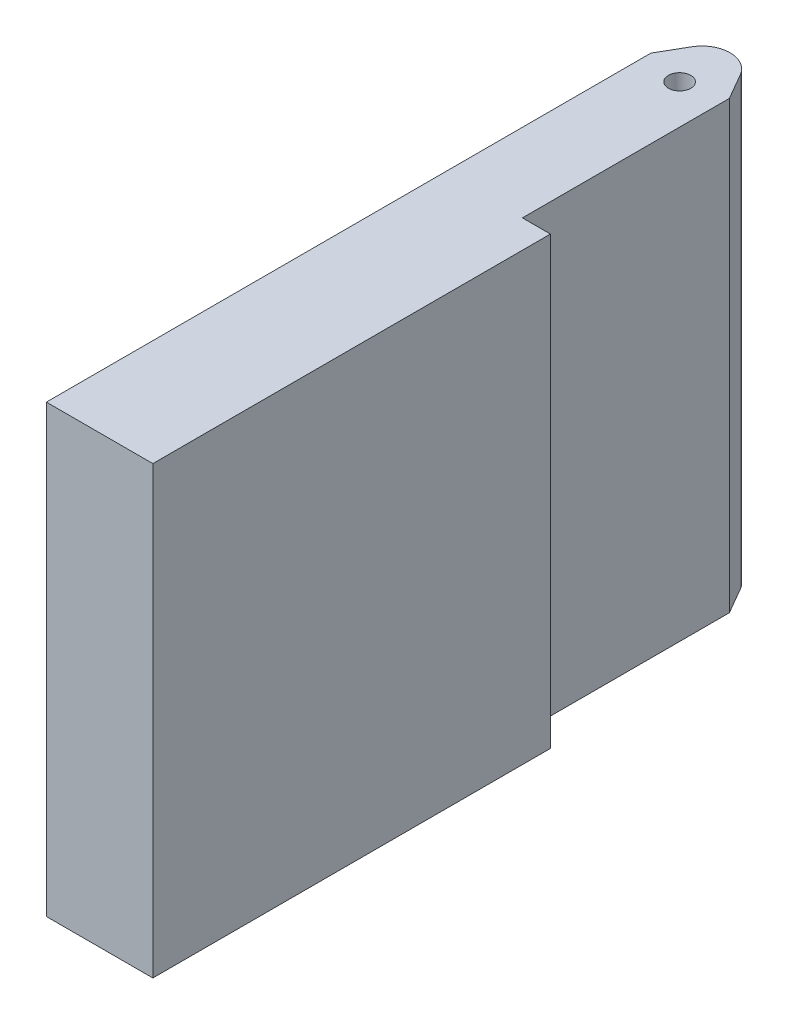
SolidWorks part; units mm, degrees
ref_plane "Front Plane" through (0, 0, 0) normal (0, 0, 1) x (1, 0, 0)
ref_plane "Top Plane" through (0, 0, 0) normal (0, 1, 0) x (1, 0, 0)
ref_plane "Right Plane" through (0, 0, 0) normal (1, 0, 0) x (0, 0, -1)
sketch "Sketch1" plane through (0, 0, 0) normal (0, 1, 0) x (1, 0, 0)
  line L1 (-11, 60) -> (11, 60)
  line L2 (-11, 60) -> (-11, -60)
  line L3 (-11, -60) -> (11, -60)
  line L4 (11, 60) -> (11, -60)
  line L5 (-11, 60) -> (11, -60) construction
  line L6 (-11, -60) -> (11, 60) construction
  point P0 (0, 0)
  dimension "D1" = 120
  dimension "D2" = 22
extrude "Boss-Extrude1" add sketch "Sketch1" along normal blind 79.5
sketch "Sketch2" plane through (0, 79.5, 0) normal (0, 1, 0) x (1, 0, 0)
  line L0 (0, 60) -> (-11, 40.9474)
  line L1 (11, 60) -> (-11, 60) construction
  line L2 (-11, 60) -> (-11, -60) construction
  line L3 (-11, 40.9474) -> (-11, -60)
  line L4 (-11, -60) -> (11, -60)
  line L5 (11, -60) -> (11, 40.9474)
  line L6 (11, -60) -> (11, 60) construction
  line L7 (11, 40.9474) -> (0, 60)
  dimension "D1" = 60
  dimension "D2" = 0
extrude "Cut-Extrude1" cut sketch "Sketch2" against normal through all flip side to cut
fillet "Fillet1" radius 5 1 edges at (0, 39.75, -60)
sketch "Sketch3" plane through (0, 79.5, 0) normal (0, 1, 0) x (1, 0, 0)
  line L0 (-11, 36.9474) -> (-7, 36.9474)
  line L1 (-11, 40.9474) -> (-11, -60) construction
  line L2 (-7, 36.9474) -> (-7, 47.8756)
  line L3 (-4.3301, 52.5) -> (-11, 40.9474) construction
  line L4 (-7, 47.8756) -> (-11, 40.9474)
  line L5 (-11, 40.9474) -> (-11, 36.9474)
  line L6 (7, 47.8756) -> (11, 40.9474)
  line L7 (11, 40.9474) -> (4.3301, 52.5) construction
  line L8 (11, 40.9474) -> (11, 36.9474)
  line L9 (11, -60) -> (11, 40.9474) construction
  line L10 (11, 36.9474) -> (7, 36.9474)
  line L11 (7, 36.9474) -> (7, 47.8756)
  dimension "D1" = 4
  dimension "D2" = 4
  dimension "D3" = 4
  dimension "D4" = 4
extrude "Cut-Extrude2" cut sketch "Sketch3" against normal through all
sketch "Sketch4" plane through (11, 0, 0) normal (1, 0, 0) x (0, 0, -1)
  line L1 (-60, 79.5) -> (36.9474, 79.5)
  line L2 (-60, 79.5) -> (-60, 0)
  line L3 (-60, 0) -> (36.9474, 0)
  line L4 (36.9474, 79.5) -> (36.9474, 0)
extrude "Boss-Extrude2" add sketch "Sketch4" along normal blind 5
sketch "Sketch5" plane through (0, 79.5, 0) normal (0, 1, 0) x (1, 0, 0)
  line L1 (-7, 36.9474) -> (-11, 36.9474)
  line L2 (-7, 36.9474) -> (-7, -60)
  line L3 (-7, -60) -> (-11, -60)
  line L4 (-11, 36.9474) -> (-11, -60)
extrude "Cut-Extrude3" cut sketch "Sketch5" against normal through all
sketch "Sketch6" plane through (0, 79.5, 0) normal (0, 1, 0) x (1, 0, 0)
  line L0 (-7, -60) -> (16, -60) construction
  line L1 (16, 36.9474) -> (12, 36.9474)
  line L2 (16, 36.9474) -> (16, -60)
  line L3 (16, -60) -> (12, -60)
  line L4 (12, 36.9474) -> (12, -60)
  dimension "D1" = 4
extrude "Cut-Extrude4" cut sketch "Sketch6" against normal through all
sketch "Sketch7" plane through (0, 79.5, 0) normal (0, 1, 0) x (1, 0, 0)
  circle A0 centre (0, 46) radius 2
  arc A1 (4.3301, 52.5) -> (-4.3301, 52.5) centre (0, 50) ccw construction
  dimension "D1" = 4
extrude "Cut-Extrude5" cut sketch "Sketch7" against normal through all
sketch "Sketch8" plane through (0, 79.5, 0) normal (0, 1, 0) x (1, 0, 0)
  line L0 (12, 36.9474) -> (12, -60) construction
  line L1 (7, 36.9474) -> (12, 36.9474)
  line L2 (7, 36.9474) -> (7, 10.9474)
  line L3 (7, 10.9474) -> (12, 10.9474)
  line L4 (12, 36.9474) -> (12, 10.9474)
  dimension "D1" = 26
extrude "Cut-Extrude6" cut sketch "Sketch8" against normal through all
